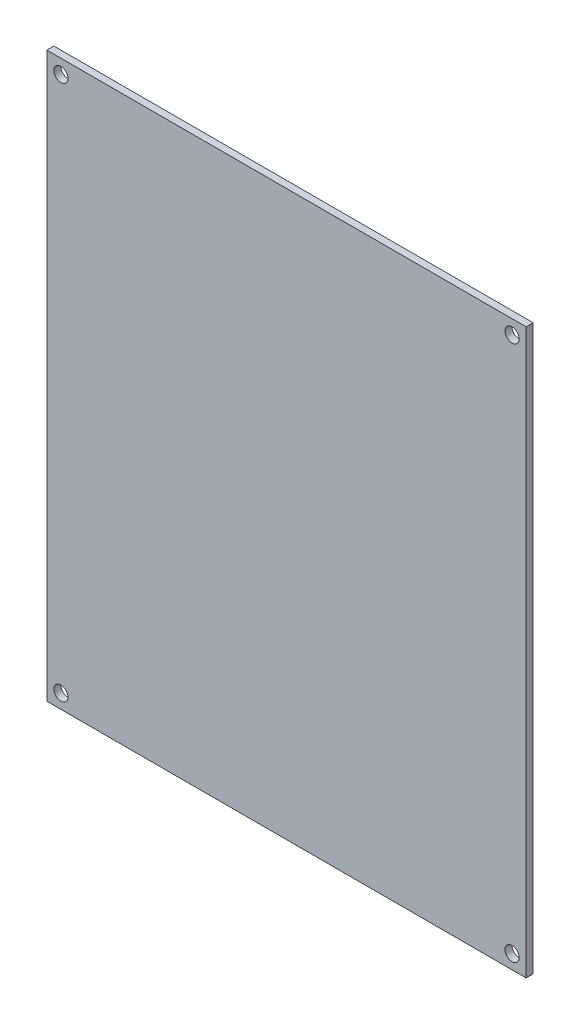
SolidWorks part; units mm, degrees
material "ABS"
ref_plane "Front Plane" through (0, 0, 0) normal (0, 0, 1) x (1, 0, 0)
ref_plane "Top Plane" through (0, 0, 0) normal (0, 1, 0) x (1, 0, 0)
ref_plane "Right Plane" through (0, 0, 0) normal (1, 0, 0) x (0, 0, -1)
ref_plane "Plane1" through (0, 0, 1.5875) normal (0, 0, 1) x (1, 0, 0)
sketch "Sketch1" plane through (0, 0, 1.5875) normal (0, 0, 1) x (1, 0, 0)
  line L0 (107.95, 0) -> (107.95, 127)
  line L1 (107.95, 127) -> (0, 127)
  line L2 (0, 127) -> (0, 0)
  line L3 (0, 0) -> (107.95, 0)
  circle A0 centre (104.775, 3.175) radius 1.5875
  circle A1 centre (3.175, 123.825) radius 1.5875
  circle A2 centre (104.775, 123.825) radius 1.5875
  circle A3 centre (3.175, 3.175) radius 1.5875
  dimension "D9" = 3.175
  dimension "D1" = 127
  dimension "D2" = 107.95
  dimension "D3" = 120.65
  dimension "D4" = 101.6
  dimension "D5" = 120.65
  dimension "D6" = 101.6
  dimension "D7" = 3.175
  dimension "D8" = 3.175
extrude "Boss-Extrude1" add sketch "Sketch1" against normal blind 1.5875
